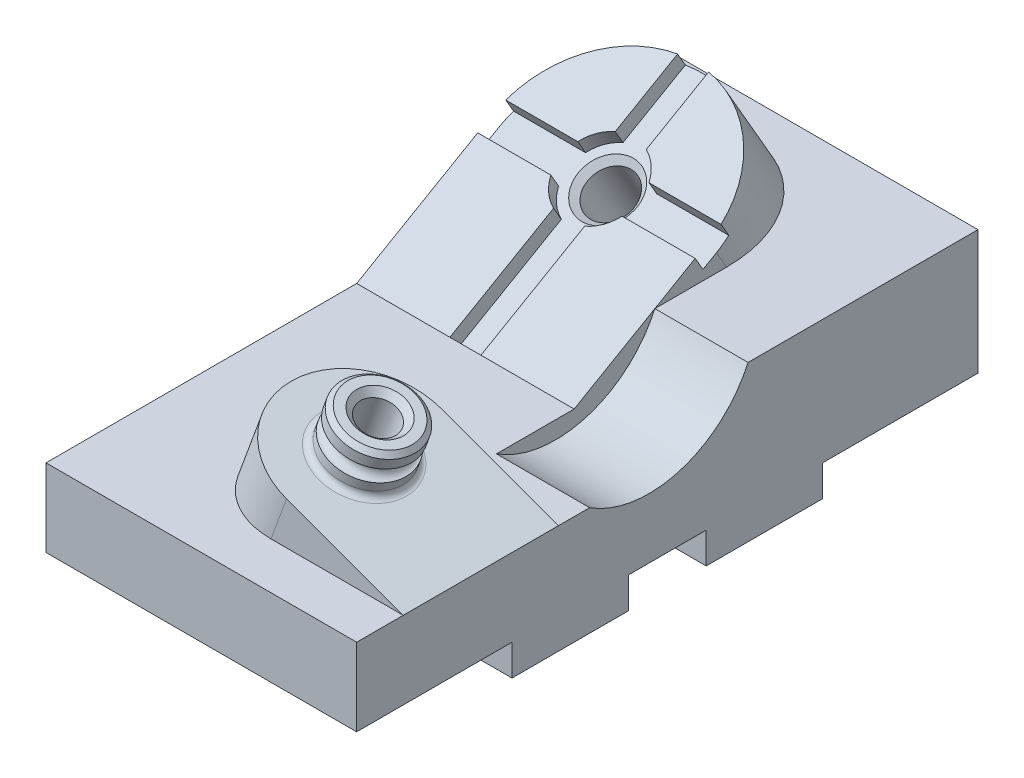
SolidWorks part; units mm, degrees
ref_plane "Front Plane" through (0, 0, 0) normal (0, 0, 1) x (1, 0, 0)
ref_plane "Top Plane" through (0, 0, 0) normal (0, 1, 0) x (1, 0, 0)
ref_plane "Right Plane" through (0, 0, 0) normal (1, 0, 0) x (0, 0, -1)
sketch "Sketch1" plane through (0, 0, 0) normal (1, 0, 0) x (0, 0, -1)
  line L0 (0, 0) -> (50, 0)
  line L1 (50, 0) -> (50, -10)
  line L2 (50, -10) -> (87.5, -10)
  line L3 (87.5, -10) -> (87.5, 0)
  line L4 (87.5, 0) -> (112.5, 0)
  line L5 (112.5, 0) -> (112.5, -10)
  line L6 (112.5, -10) -> (150, -10)
  line L7 (150, -10) -> (150, 0)
  line L8 (150, 0) -> (200, 0)
  line L9 (0, 0) -> (0, 25)
  line L10 (0, 25) -> (100, 25)
  line L11 (200, 0) -> (200, 40)
  line L12 (200, 40) -> (125.9808, 40)
  line L13 (100, 25) -> (125.9808, 40)
  dimension "D1" = 200
  dimension "D2" = 37.5
  dimension "D3" = 37.5
  dimension "D4" = 10
  dimension "D5" = 50
  dimension "D6" = 25
  dimension "D7" = 40
  dimension "D8" = 30
  dimension "D9" = 100
extrude "Boss-Extrude1" add sketch "Sketch1" along normal blind 100
sketch "Sketch2" plane through (100, 0, 0) normal (1, 0, 0) x (0, 0, -1)
  line L1 (125.9808, 40) -> (100, 25) construction
  line L2 (100, 25) -> (75, 25)
  line L3 (125.9808, 40) -> (100, 25)
  arc A0 (125.9808, 40) -> (75, 25) centre (94.06, 54.355) cw
  dimension "D3" = 35
  dimension "D1" = 25
  dimension "D2" = 100
extrude "Cut-Extrude1" cut sketch "Sketch2" against normal blind 30
sketch "Sketch3" plane through (0, 0, 0) normal (0, 0, 1) x (1, 0, 0)
  line L0 (100, 25) -> (0, 25) construction
  line L1 (100, 25) -> (30.8284, 25)
  line L2 (100, 25) -> (38.92, 47.2313)
  line L3 (38.92, 47.2313) -> (30.8284, 25)
  dimension "D1" = 65
  dimension "D2" = 20
extrude "Boss-Extrude2" add sketch "Sketch3" against normal blind 50 from offset 15 offset against normal yes
sketch "Sketch4" plane through (19.7326, 54.2149, 0) normal (0.342, 0.9397, 0) x (0.9397, -0.342, 0)
  line L4 (45.4188, 65) -> (20.4188, 65)
  line L5 (20.4188, 65) -> (20.4188, 15)
  line L6 (20.4188, 65) -> (20.4188, 15) construction
  line L7 (20.4188, 15) -> (45.4188, 15)
  arc A1 (45.4188, 65) -> (45.4188, 15) centre (45.4188, 40) ccw
  line M2 (20.4188, 15) -> (85.4188, 15)
  line M4 (85.4188, 65) -> (20.4188, 65)
  line M5 (20.4188, 65) -> (20.4188, 15)
  dimension "D1" = 25
extrude "Cut-Extrude2" cut sketch "Sketch4" against normal up to surface (23.6581 mm away) contours A1 M4 M5 | A1 L5 M2
sketch "Sketch5" plane through (19.7326, 54.2149, 0) normal (0.342, 0.9397, 0) x (0.9397, -0.342, 0)
  circle A0 centre (45.4188, 40) radius 12.5
  dimension "D1" = 25
extrude "Boss-Extrude4" add sketch "Sketch5" along normal blind 15
sketch "Sketch7" plane through (24.8629, 68.3103, 0) normal (0.342, 0.9397, 0) x (0.9397, -0.342, 0)
  circle A0 centre (45.4188, 40) radius 6
  dimension "D1" = 12
extrude "Cut-Extrude4" cut sketch "Sketch7" against normal through all
fillet "Fillet1" radius 2 1 edges at (50.6661, 42.9561, -40)
chamfer "Chamfer1" distance 2 angle 45 1 edges at (61.9044, 54.8283, -40)
ref_plane "Plane1" through (42.6797, -15.5341, 0) normal (0.9397, -0.342, 0) x (0.342, 0.9397, 0)
sketch "Sketch11" plane through (42.6797, -15.5341, 0) normal (0.9397, -0.342, 0) x (0.342, 0.9397, 0)
  line L0 (72.6943, -27.5) -> (59.6943, -27.5) construction
  line L1 (67.6943, -27.5) -> (62.6943, -27.5)
  line L2 (72.6943, -27.5) -> (59.6943, -27.5) construction
  line L5 (72.6943, -52.5) -> (72.6943, -27.5) construction
  arc A0 (62.6943, -27.5) -> (67.6943, -27.5) centre (65.1943, -27.5) ccw
  dimension "D1" = 7.5
  dimension "D2" = 2.5
revolve "Cut-Revolve1" cut sketch "Sketch11" angle 360 about axis through (43.3966, -13.5645, -40) along (0.342, 0.9397, 0)
chamfer "Chamfer2" distance 1.5 angle 45 1 edges at (55.7964, 57.0514, -40)
sketch "Sketch13" plane through (0, 0, 0) normal (-1, 0, 0) x (0, 0, 1)
  line L0 (-125.9808, 40) -> (-173.6122, 67.5)
  line L1 (-173.6122, 67.5) -> (-189.4893, 40)
  line L2 (-200, 40) -> (-125.9808, 40) construction
  line L3 (-189.4893, 40) -> (-125.9808, 40)
  dimension "D1" = 55
  dimension "D2" = 30
extrude "Boss-Extrude5" add sketch "Sketch13" against normal blind 70
sketch "Sketch14" plane through (0, -24.5513, -14.1747) normal (0, 0.866, 0.5) x (1, 0, 0)
  line L1 (0, 149.1025) -> (0, 184.1025)
  line L2 (0, 184.1025) -> (70, 184.1025)
  line L3 (70, 184.1025) -> (70, 149.1025)
  arc A1 (70, 149.1025) -> (0, 149.1025) centre (35, 149.1025) ccw
  line M3 (70, 129.1025) -> (70, 184.1025)
  line M4 (70, 184.1025) -> (0, 184.1025)
  line M5 (0, 184.1025) -> (0, 99.1025)
extrude "Cut-Extrude5" cut sketch "Sketch14" against normal up to surface (31.7543 mm away) contours A1 M3 M4 | A1 L2 M5
sketch "Sketch15" plane through (0, -24.5513, -14.1747) normal (0, 0.866, 0.5) x (1, 0, 0)
  line L1 (70, 99.1025) -> (0, 99.1025) construction
  line L2 (30, 183.7436) -> (30, 160.559)
  line L3 (40, 183.7436) -> (40, 160.559)
  line L5 (0, 144.1025) -> (23.5436, 144.1025)
  line L6 (0.359, 154.1025) -> (23.5436, 154.1025)
  line L8 (46.4564, 154.1025) -> (69.641, 154.1025)
  line L9 (40, 137.6461) -> (40, 99.1025)
  line L11 (30, 137.6461) -> (30, 99.1025)
  line L12 (0, 149.1025) -> (0, 99.1025) construction
  line L13 (0, 149.1025) -> (0, 144.1025)
  line L14 (70, 129.1025) -> (70, 149.1025) construction
  line L15 (70, 144.1025) -> (70, 149.1025)
  line L16 (40, 99.1025) -> (30, 99.1025)
  line L17 (70, 129.1025) -> (70, 99.1025) construction
  line L18 (70, 129.1025) -> (70, 99.1025)
  line L20 (46.4564, 144.1025) -> (70, 144.1025)
  arc A0 (70, 149.1025) -> (0, 149.1025) centre (35, 149.1025) ccw construction
  arc A1 (23.5436, 144.1025) -> (30, 137.6461) centre (35, 149.1025) ccw
  arc A2 (70, 149.1025) -> (69.641, 154.1025) centre (35, 149.1025) ccw
  arc A3 (30, 160.559) -> (23.5436, 154.1025) centre (35, 149.1025) ccw
  arc A4 (46.4564, 154.1025) -> (40, 160.559) centre (35, 149.1025) ccw
  arc A5 (40, 137.6461) -> (46.4564, 144.1025) centre (35, 149.1025) ccw
  arc A6 (0.359, 154.1025) -> (0, 149.1025) centre (35, 149.1025) ccw
  arc A7 (40, 183.7436) -> (30, 183.7436) centre (35, 149.1025) ccw
  arc M2 (70, 149.1025) -> (0, 149.1025) centre (35, 149.1025) ccw
  line M3 (0, 149.1025) -> (0, 99.1025)
  line M4 (0, 99.1025) -> (70, 99.1025)
  line M6 (70, 129.1025) -> (70, 149.1025)
  dimension "D1" = 12.5
  dimension "D3" = 10
  dimension "D2" = 10
extrude "Cut-Extrude6" cut sketch "Sketch15" against normal blind 5 contours L9 A5 L20 L8 A4 L3 L2 A3 L6 L5 A1 L11 M6 M2 M3 M4
sketch "Sketch17" plane through (0, -28.8814, -16.6747) normal (0, 0.866, 0.5) x (1, 0, 0)
  circle A0 centre (35, 149.1025) radius 7.5
  dimension "D1" = 15
extrude "Cut-Extrude7" cut sketch "Sketch17" against normal through all both and the other way through all
chamfer "Chamfer3" distance 2 angle 45 1 edges at (35, 41.9199, -139.3061)
